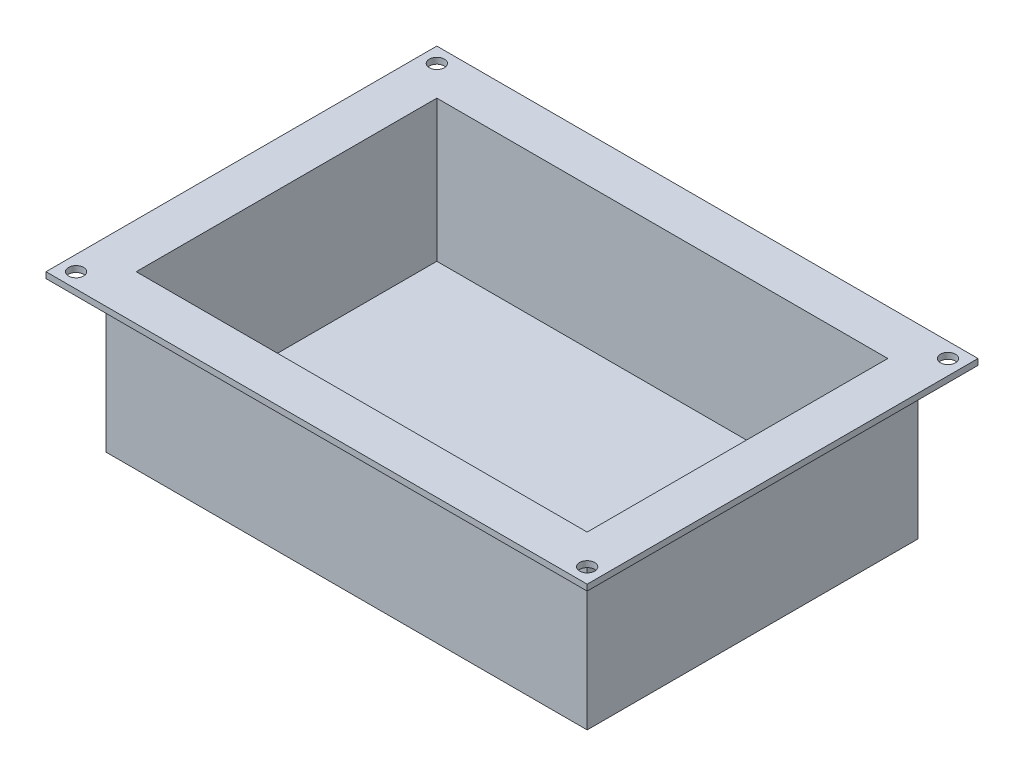
SolidWorks part; units mm, degrees
ref_plane "Front Plane" through (0, 0, 0) normal (0, 0, 1) x (1, 0, 0)
ref_plane "Top Plane" through (0, 0, 0) normal (0, 1, 0) x (1, 0, 0)
ref_plane "Right Plane" through (0, 0, 0) normal (1, 0, 0) x (0, 0, -1)
sketch "Sketch1" plane through (0, 0, 0) normal (0, 1, 0) x (1, 0, 0)
  line L0 (-114.3, 82.55) -> (114.3, 82.55)
  line L1 (-101.6, 69.85) -> (101.6, 69.85)
  line L2 (-101.6, 69.85) -> (-101.6, -69.85)
  line L3 (-101.6, -69.85) -> (101.6, -69.85)
  line L4 (101.6, 69.85) -> (101.6, -69.85)
  line L5 (-101.6, 69.85) -> (101.6, -69.85) construction
  line L6 (-101.6, -69.85) -> (101.6, 69.85) construction
  line L7 (114.3, 82.55) -> (114.3, -82.55)
  line L8 (-114.3, -82.55) -> (114.3, -82.55)
  line L9 (-114.3, 82.55) -> (-114.3, -82.55)
  point P0 (0, 0)
  dimension "D1" = 203.2
  dimension "D2" = 139.7
  dimension "D3" = 12.7
extrude "Boss-Extrude2" add sketch "Sketch1" along normal blind 63.5 contours L2 L1 L4 L3
sketch "Sketch3" plane through (0, 63.5, 0) normal (0, 1, 0) x (1, 0, 0)
  line L8 (-114.3, -82.55) -> (114.3, -82.55)
  line L9 (114.3, -82.55) -> (114.3, 82.55)
  line L10 (114.3, 82.55) -> (-114.3, 82.55)
  line L11 (-114.3, 82.55) -> (-114.3, -82.55)
  line L12 (-114.3, -82.55) -> (114.3, -82.55)
  line L13 (114.3, -82.55) -> (114.3, 82.55)
  line L14 (114.3, 82.55) -> (-114.3, 82.55)
  line L15 (-114.3, 82.55) -> (-114.3, -82.55)
  dimension "D1" = 12.7
extrude "Boss-Extrude3" add sketch "Sketch3" along normal blind 2.54
hole_wizard "1/4 (0.25) Diameter Hole1" positions "3DSketch9" profile "Sketch7" hole size "1/4" standard "ANSI Inch" end condition through all
sketch3d "3DSketch9"
  line L0 (114.3, 63.5, -82.55) -> (-114.3, 63.5, -82.55) construction
  line L1 (114.3, 63.5, 82.55) -> (114.3, 63.5, -82.55) construction
  line L3 (-114.3, 63.5, 82.55) -> (114.3, 63.5, 82.55) construction
  line L4 (-114.3, 63.5, -82.55) -> (-114.3, 63.5, 82.55) construction
  point P0 (107.95, 63.5, -76.2)
  point P2 (107.95, 63.5, 76.2)
  point P4 (-107.95, 63.5, -76.2)
  point P6 (-107.95, 63.5, 76.2)
  dimension "D1" = 6.35
  dimension "D2" = 6.35
  dimension "D3" = 6.35
  dimension "D4" = 6.35
  dimension "D5" = 6.35
  dimension "D6" = 6.35
  dimension "D7" = 6.35
  dimension "D8" = 6.35
sketch "Sketch7" plane through (107.95, 63.5, -76.2) normal (1, 0, 0) x (0, 0, -1)
  line L0 (0, 0) -> (0, 2.54)
  line L1 (0, 2.54) -> (3.175, 2.54)
  line L2 (3.175, 2.54) -> (3.175, 0)
  line L5 (3.175, 0) -> (0, 0)
  line L11 (0, -6.35) -> (0, 107.95) construction
  dimension "Thru Hole Dia." = 6.35
  dimension "Thru Hole Depth" = 2.54
sketch "Sketch9" plane through (0, 66.04, 0) normal (0, 1, 0) x (1, 0, 0)
  line L12 (-95.25, -63.5) -> (95.25, -63.5)
  line L13 (-95.25, 63.5) -> (-95.25, -63.5)
  line L14 (95.25, 63.5) -> (-95.25, 63.5)
  line L15 (95.25, -63.5) -> (95.25, 63.5)
  line L16 (-95.25, -63.5) -> (95.25, -63.5)
  line L17 (-95.25, 63.5) -> (-95.25, -63.5)
  line L18 (95.25, 63.5) -> (-95.25, 63.5)
  line L19 (95.25, -63.5) -> (95.25, 63.5)
  dimension "D1" = 6.35
sketch "Sketch10" plane through (0, 66.04, 0) normal (0, 1, 0) x (1, 0, 0)
  line L1 (-95.25, 63.5) -> (95.25, 63.5)
  line L2 (-95.25, 63.5) -> (-95.25, -63.5)
  line L3 (-95.25, -63.5) -> (95.25, -63.5)
  line L4 (95.25, 63.5) -> (95.25, -63.5)
extrude "Cut-Extrude1" cut sketch "Sketch10" along direction (0, -1, 0) on the side against the normal offset from surface (59.69 mm away) 6.35
